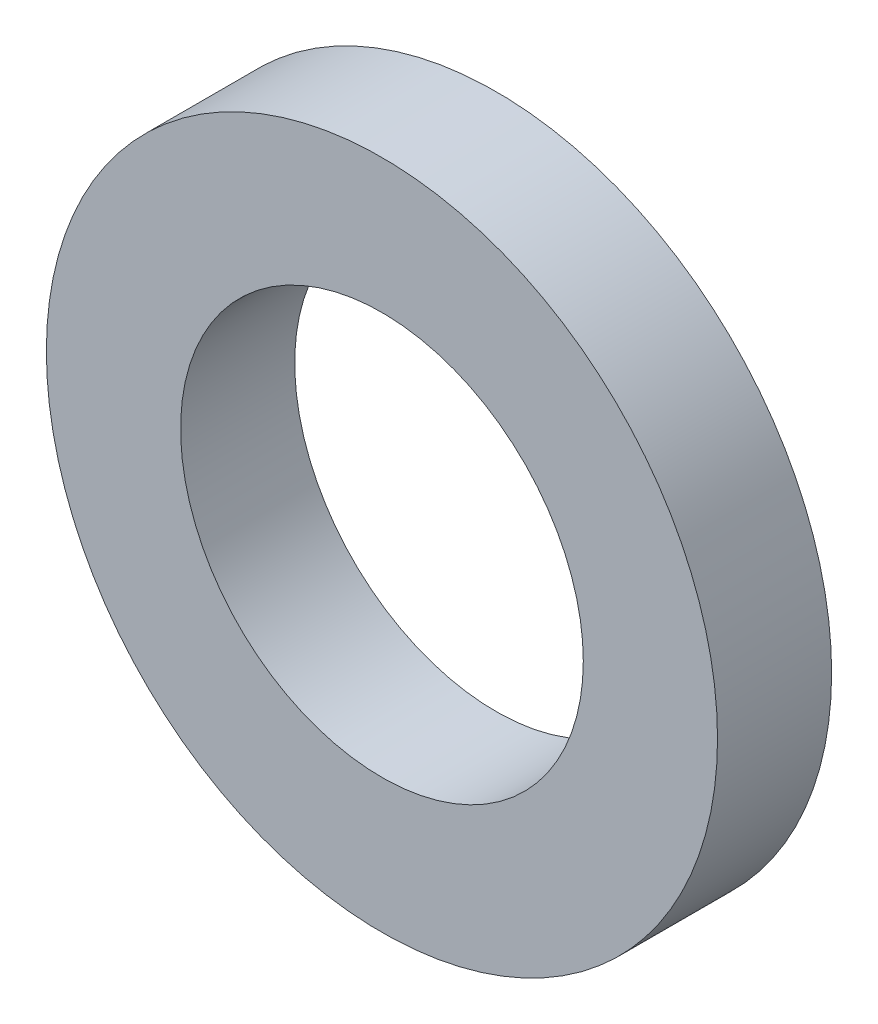
SolidWorks part; units mm, degrees
ref_plane "Front Plane" through (0, 0, 0) normal (0, 0, 1) x (1, 0, 0)
ref_plane "Top Plane" through (0, 0, 0) normal (0, 1, 0) x (1, 0, 0)
ref_plane "Right Plane" through (0, 0, 0) normal (1, 0, 0) x (0, 0, -1)
sketch "Sketch1" plane through (0, 0, 0) normal (0, 0, 1) x (1, 0, 0)
  circle A0 centre (0, 0) radius 3
  circle A1 centre (0, 0) radius 5
  dimension "D1" = 6
  dimension "D2" = 10
extrude "Boss-Extrude1" add sketch "Sketch1" along normal blind 1.7
equation "\"smallPulleyTeeth\"= 15"
equation "\"largePulleyTeeth\"= 30"
equation "\"eighthThick\"= 2.9mm"
equation "\"sixteenthThick\" = 1.7mm"
equation "\"quarterThick\"=5.9mm"
equation "\"OD\" = 145mm"
equation "\"puckAngle\" = 60.5deg"
equation "\"puckDiam\" = 76.5mm"
equation "\"axlePress\" = 5.9mm"
equation "\"press\" = 0.2mm"
equation "\"wheelClear\" = 0.3mm"
equation "\"10-32clear\" = 4.5mm"
equation "\"6-32clear\" = 3.3mm"
equation "\"8-32clear\" = 4.0mm"
equation "\"D1@Boss-Extrude1\"=\"sixteenthThick\""
